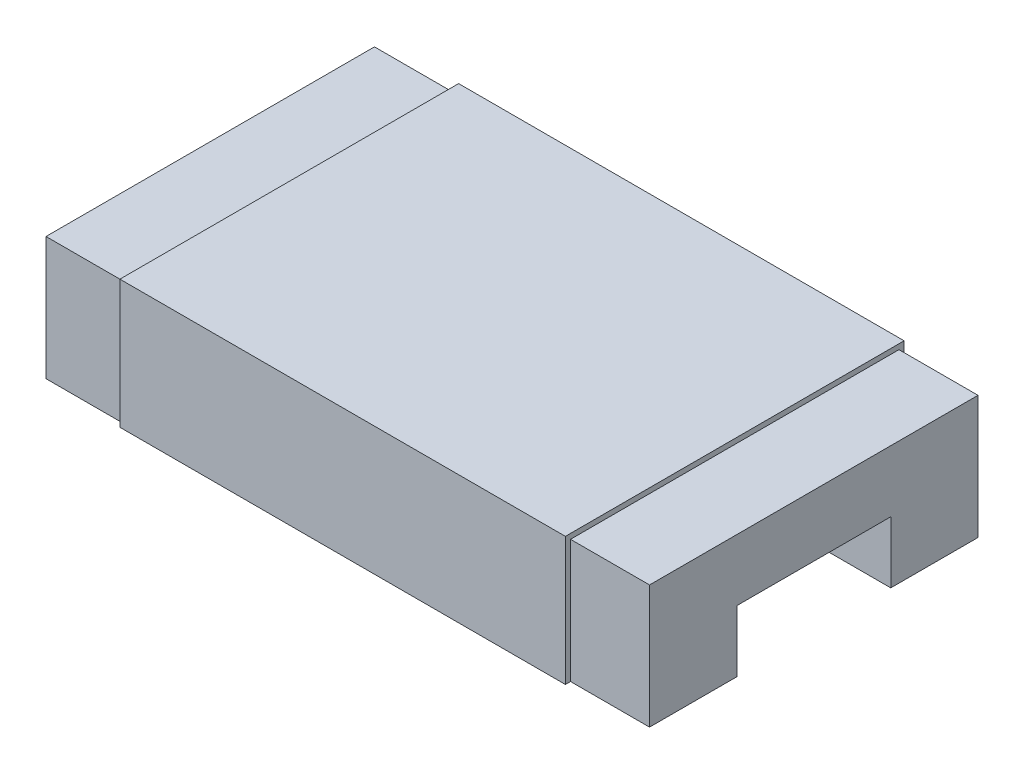
SolidWorks part; units mm, degrees
ref_plane "Płaszczyzna przednia" through (0, 0, 0) normal (0, 0, 1) x (1, 0, 0)
ref_plane "Płaszczyzna górna" through (0, 0, 0) normal (0, 1, 0) x (1, 0, 0)
ref_plane "Płaszczyzna prawa" through (0, 0, 0) normal (1, 0, 0) x (0, 0, -1)
sketch "Sketch1" plane through (0, 0, 0) normal (1, 0, 0) x (0, 0, -1)
  line L0 (0, 0) -> (0, 24.8575) construction
  line L1 (-16, 6) -> (16, 6)
  line L2 (16, 6) -> (16, -6)
  line L3 (16, -6) -> (7.5, -6)
  line L4 (7.5, -6) -> (7.5, 0)
  line L5 (7.5, 0) -> (-7.5, 0)
  line L6 (-7.5, -6) -> (-7.5, 0)
  line L7 (-16, 6) -> (-16, -6)
  line L8 (-16, -6) -> (-7.5, -6)
  point P5 (16, 0)
  point P9 (8.5291, 0)
  point P10 (0, 0.4477)
  point P14 (0, 6)
  dimension "D1" = 32
  dimension "D2" = 12
  dimension "D3" = 15
extrude "Boss-Extrude1" add sketch "Sketch1" along normal mid plane 58.8
sketch "Sketch2" plane through (0, 0, 0) normal (1, 0, 0) x (0, 0, -1)
  line L0 (-16, -6) -> (-16.5, -6)
  line L1 (-16.5, -6) -> (-16.5, 6.5)
  line L2 (-16.5, 6.5) -> (16.5, 6.5)
  line L3 (16.5, 6.5) -> (16.5, -6)
  line L4 (16.5, -6) -> (16, -6)
  line L5 (16, 6) -> (-16, 6) construction
  line L6 (16, -6) -> (16, 6) construction
  line L7 (-16, 6) -> (-16, -6) construction
  line L8 (16, -6) -> (16, 6)
  line L9 (16, 6) -> (-16, 6)
  line L10 (-16, 6) -> (-16, -6)
  dimension "D1" = 0.5
  dimension "D2" = 0.5
  dimension "D3" = 0.5
extrude "Boss-Extrude2" add sketch "Sketch2" along normal mid plane 43.4
